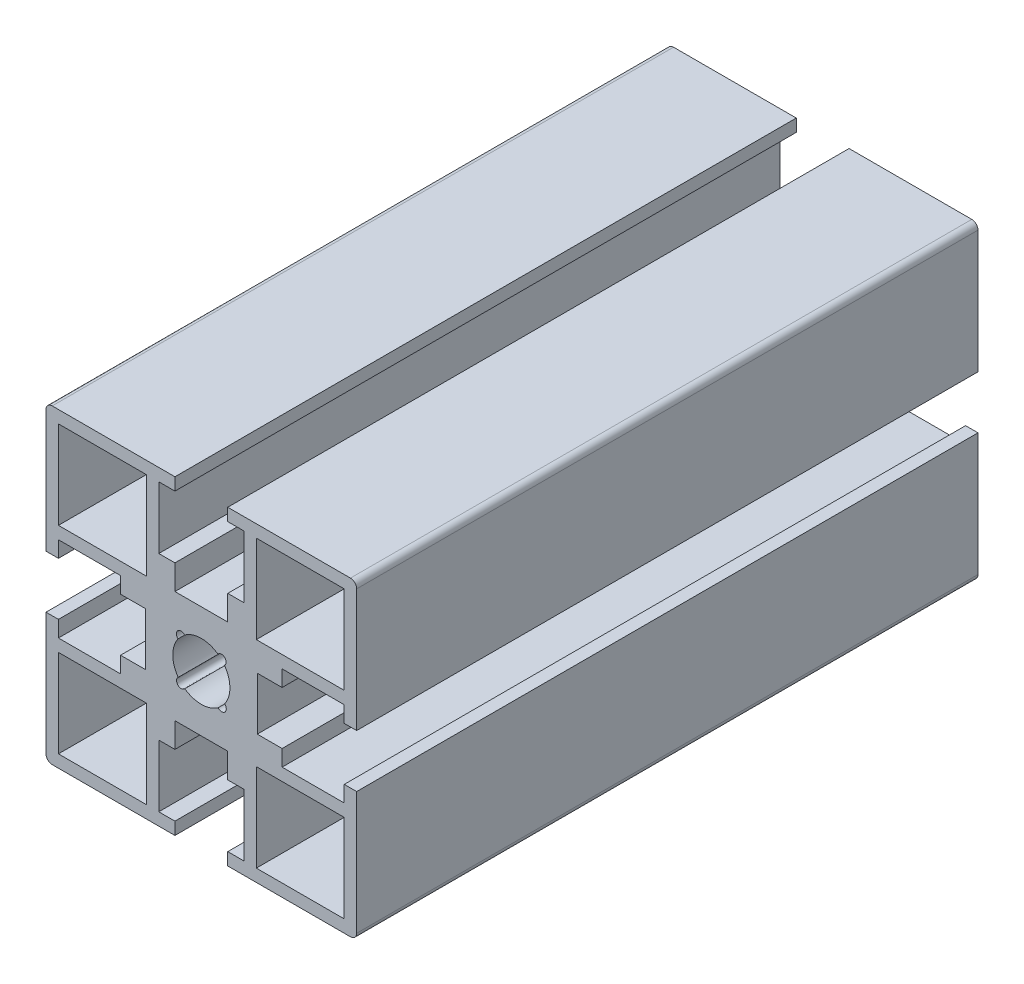
SolidWorks part; units mm, degrees
ref_plane "前视基准面" through (0, 0, 0) normal (0, 0, 1) x (1, 0, 0)
ref_plane "上视基准面" through (0, 0, 0) normal (0, 1, 0) x (1, 0, 0)
ref_plane "右视基准面" through (0, 0, 0) normal (1, 0, 0) x (0, 0, -1)
sketch "草图1" plane through (0, 0, 0) normal (0, 0, 1) x (1, 0, 0)
  line B0 (-25, 24) -> (-25, 4.25)
  line B1 (-25, 4.25) -> (-23, 4.25)
  line B2 (-23, 4.25) -> (-23, 6.85)
  line B3 (-23, 6.85) -> (-13, 6.85)
  line B4 (-13, 6.85) -> (-13, 4.25)
  line B5 (-13, 4.25) -> (-9, 4.25)
  line B6 (-9, 4.25) -> (-9, -4.25)
  line B7 (-9, -4.25) -> (-13, -4.25)
  line B8 (-13, -4.25) -> (-13, -6.85)
  line B9 (-13, -6.85) -> (-23, -6.85)
  line B10 (-23, -6.85) -> (-23, -4.25)
  line B11 (-23, -4.25) -> (-25, -4.25)
  line B12 (-25, -4.25) -> (-25, -24)
  line B13 (-24, -25) -> (-4.25, -25)
  line B14 (-4.25, -25) -> (-4.25, -23)
  line B15 (-4.25, -23) -> (-6.85, -23)
  line B16 (-6.85, -23) -> (-6.85, -13)
  line B17 (-6.85, -13) -> (-4.25, -13)
  line B18 (-4.25, -13) -> (-4.25, -9)
  line B19 (-4.25, -9) -> (4.25, -9)
  line B20 (4.25, -9) -> (4.25, -13)
  line B21 (4.25, -13) -> (6.85, -13)
  line B22 (6.85, -13) -> (6.85, -23)
  line B23 (6.85, -23) -> (4.25, -23)
  line B24 (4.25, -23) -> (4.25, -25)
  line B25 (4.25, -25) -> (24, -25)
  line B26 (25, -24) -> (25, -4.25)
  line B27 (25, -4.25) -> (23, -4.25)
  line B28 (23, -4.25) -> (23, -6.85)
  line B29 (23, -6.85) -> (13, -6.85)
  line B30 (13, -6.85) -> (13, -4.25)
  line B31 (13, -4.25) -> (9, -4.25)
  line B32 (9, -4.25) -> (9, 4.25)
  line B33 (9, 4.25) -> (13, 4.25)
  line B34 (13, 4.25) -> (13, 6.85)
  line B35 (13, 6.85) -> (23, 6.85)
  line B36 (23, 6.85) -> (23, 4.25)
  line B37 (23, 4.25) -> (25, 4.25)
  line B38 (25, 4.25) -> (25, 24)
  line B39 (24, 25) -> (4.25, 25)
  line B40 (4.25, 25) -> (4.25, 23)
  line B41 (4.25, 23) -> (6.85, 23)
  line B42 (6.85, 23) -> (6.85, 13)
  line B43 (6.85, 13) -> (4.25, 13)
  line B44 (4.25, 13) -> (4.25, 9)
  line B45 (4.25, 9) -> (-4.25, 9)
  line B46 (-4.25, 9) -> (-4.25, 13)
  line B47 (-4.25, 13) -> (-6.85, 13)
  line B48 (-6.85, 13) -> (-6.85, 23)
  line B49 (-6.85, 23) -> (-4.25, 23)
  line B50 (-4.25, 23) -> (-4.25, 25)
  line B51 (-4.25, 25) -> (-24, 25)
  line B52 (23, 23) -> (23, 8.85)
  line B53 (23, 8.85) -> (8.85, 8.85)
  line B54 (8.85, 8.85) -> (8.85, 23)
  line B55 (8.85, 23) -> (23, 23)
  line B56 (8.85, -23) -> (8.85, -8.85)
  line B57 (8.85, -8.85) -> (23, -8.85)
  line B58 (23, -8.85) -> (23, -23)
  line B59 (23, -23) -> (8.85, -23)
  line B60 (-8.85, -23) -> (-23, -23)
  line B61 (-23, -23) -> (-23, -8.85)
  line B62 (-23, -8.85) -> (-8.85, -8.85)
  line B63 (-8.85, -8.85) -> (-8.85, -23)
  line B64 (-23, 23) -> (-8.85, 23)
  line B65 (-8.85, 23) -> (-8.85, 8.85)
  line B66 (-8.85, 8.85) -> (-23, 8.85)
  line B67 (-23, 8.85) -> (-23, 23)
  arc B68 (-25, -24) -> (-24, -25) centre (-24, -24) ccw
  arc B69 (24, -25) -> (25, -24) centre (24, -24) ccw
  arc B70 (25, 24) -> (24, 25) centre (24, 24) ccw
  arc B71 (-24, 25) -> (-25, 24) centre (-24, 24) ccw
  arc B72 (-3.7492, 2.6652) -> (-3.7267, -2.6966) centre (0, 0) ccw
  arc B73 (-3.7267, -2.6966) -> (-2.6652, -3.7492) centre (-3.239, -3.2663) ccw
  arc B74 (-2.6652, -3.7492) -> (2.6966, -3.7267) centre (0, 0) ccw
  arc B75 (2.6966, -3.7267) -> (3.7492, -2.6652) centre (3.2663, -3.239) ccw
  arc B76 (3.7492, -2.6652) -> (3.7267, 2.6966) centre (0, 0) ccw
  arc B77 (3.7267, 2.6966) -> (2.6652, 3.7492) centre (3.239, 3.2663) ccw
  arc B78 (2.6652, 3.7492) -> (-2.6966, 3.7267) centre (0, 0) ccw
  arc B79 (-2.6966, 3.7267) -> (-3.7492, 2.6652) centre (-3.2663, 3.239) ccw
sketch_block_instance "A$C19A9285B-1"
sketch_block "A$C19A9285B"
extrude "凸台-拉伸1" add sketch "草图1" along normal blind 100
